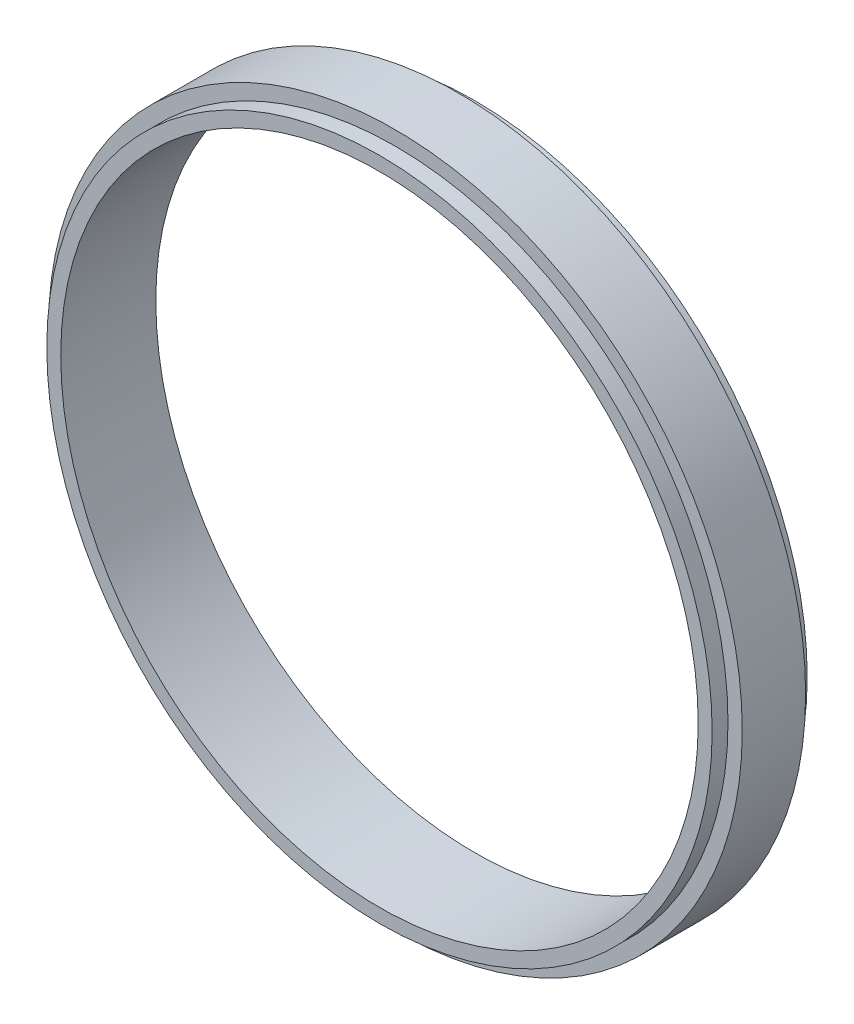
SolidWorks part; units mm, degrees
ref_plane "Front Plane" through (0, 0, 0) normal (0, 0, 1) x (1, 0, 0)
ref_plane "Top Plane" through (0, 0, 0) normal (0, 1, 0) x (1, 0, 0)
ref_plane "Right Plane" through (0, 0, 0) normal (1, 0, 0) x (0, 0, -1)
sketch "S01 - Inner race contact lips" plane through (0, 0, 0) normal (0, 0, 1) x (1, 0, 0)
  circle A0 centre (0, 0) radius 21
  circle A1 centre (0, 0) radius 20.12
  dimension "D1" = 40.24
  dimension "D2" = 42
extrude "01 - Inner race contact lips" add sketch "S01 - Inner race contact lips" along normal blind 6
sketch "S02 - Stiffened middle of spacer" plane through (0, 0, 0) normal (0, 0, 1) x (1, 0, 0)
  circle A0 centre (0, 0) radius 21.9
  circle A1 centre (0, 0) radius 20.12
  dimension "D1" = 40.24
  dimension "D2" = 43.8
extrude "02 - Stiffened middle of spacer" add sketch "S02 - Stiffened middle of spacer" along normal blind 4 from offset 1
